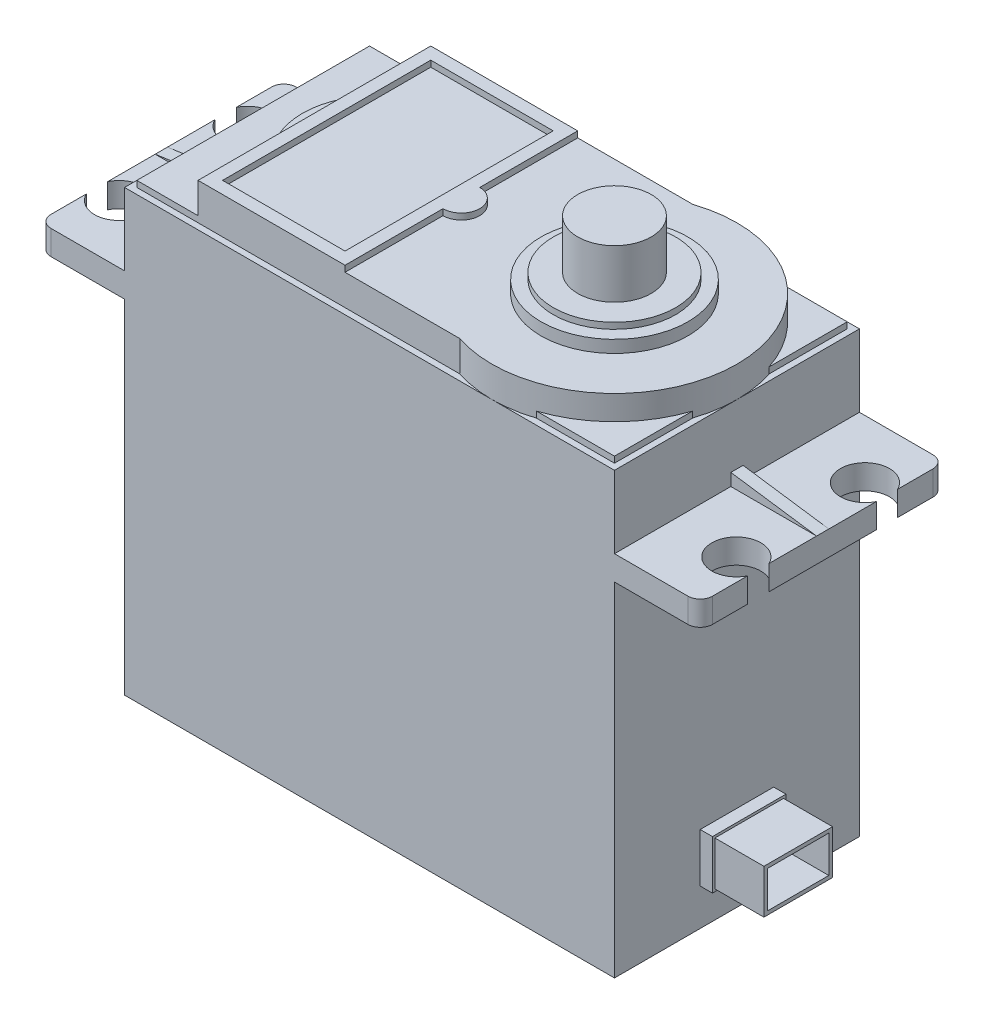
SolidWorks part; units mm, degrees
ref_plane "Front Plane" through (0, 0, 0) normal (0, 0, 1) x (1, 0, 0)
ref_plane "Top Plane" through (0, 0, 0) normal (0, 1, 0) x (1, 0, 0)
ref_plane "Right Plane" through (0, 0, 0) normal (1, 0, 0) x (0, 0, -1)
sketch "Sketch1" plane through (0, 0, 0) normal (0, 1, 0) x (1, 0, 0)
  line L1 (0, 0) -> (40, 0)
  line L2 (0, 0) -> (0, 20)
  line L3 (0, 20) -> (40, 20)
  line L4 (40, 0) -> (40, 20)
  dimension "D1" = 40
  dimension "D2" = 20
extrude "Boss-Extrude1" add sketch "Sketch1" along normal blind 35.9
sketch "Sketch2" plane through (0, 0, 0) normal (1, 0, 0) x (0, 0, -1)
  line L0 (0, 35.9) -> (0, 0) construction
  line L1 (0, 28) -> (20, 28)
  line L2 (0, 28) -> (0, 30)
  line L3 (0, 30) -> (20, 30)
  line L4 (20, 28) -> (20, 30)
  line L5 (20, 35.9) -> (20, 0) construction
  line L7 (0, 0) -> (20, 0) construction
  dimension "D1" = 28
  dimension "D2" = 2
extrude "Boss-Extrude2" add sketch "Sketch2" against normal blind 7
sketch "Sketch3" plane through (0, 30, 0) normal (0, 1, 0) x (1, 0, 0)
  line L0 (-7, 20) -> (-7, 0) construction
  line L1 (-7, 10.5) -> (0, 10.5)
  line L2 (-7, 10.5) -> (-7, 9.5)
  line L3 (-7, 9.5) -> (0, 9.5)
  line L4 (0, 10.5) -> (0, 9.5)
  line L5 (0, 20) -> (0, 0) construction
  line L6 (-7, 20) -> (-7, 0) construction
  point P8 (-7, 10)
  point P9 (-7, 10)
  dimension "D1" = 1
extrude "Boss-Extrude3" add sketch "Sketch3" along normal blind 1
sketch "Sketch4" plane through (0, 30, 0) normal (0, 1, 0) x (1, 0, 0)
  line L1 (-7, 20) -> (-7, 10.5) construction
  line L3 (-7, 10.5) -> (-7, 9.5) construction
  line L4 (-7, 10) -> (0, 10) construction
  line L5 (0, 20) -> (0, 0) construction
  circle A0 centre (-5.2, 15.25) radius 2
  circle A1 centre (-5.2, 4.75) radius 2
  point P3 (-7, 15.25)
  dimension "D1" = 4
  dimension "D2" = 1.8
extrude "Cut-Extrude1" cut sketch "Sketch4" against normal up to next
fillet "Fillet1" radius 1 2 edges at (-7, 29, 0) (-7, 29, -20)
sketch "Sketch5" plane through (0, 0, -9.5) normal (0, 0, 1) x (1, 0, 0)
  line L0 (-7, 30) -> (0, 31)
  line L5 (-7, 30) -> (-7, 31)
  line L6 (-7, 31) -> (0, 31)
extrude "Cut-Extrude2" cut sketch "Sketch5" against normal blind 11
ref_plane "Plane1" through (20, 0, 0) normal (1, 0, 0) x (0, 0, -1)
mirror "Mirror1" about plane through (20, 0, 0) normal (1, 0, 0) of "Cut-Extrude2", "Fillet1", "Cut-Extrude1", "Boss-Extrude3", "Boss-Extrude2"
sketch "Sketch6" plane through (0, 35.9, 0) normal (0, 1, 0) x (1, 0, 0)
  line L4 (0, 20) -> (0, 0) construction
  line L32 (0.5, 19.5) -> (0.5, 0.5)
  line L33 (0.5, 0.5) -> (39.5, 0.5)
  line L34 (39.5, 0.5) -> (39.5, 19.5)
  line L35 (39.5, 19.5) -> (0.5, 19.5)
  line L36 (0.5, 19.5) -> (0.5, 0.5)
  line L37 (0.5, 0.5) -> (39.5, 0.5)
  line L38 (39.5, 0.5) -> (39.5, 19.5)
  line L39 (39.5, 19.5) -> (0.5, 19.5)
  point P2 (0, 10)
  point P3 (0, 0)
  dimension "D1" = 0.5
extrude "Boss-Extrude4" add sketch "Sketch6" along normal blind 0.5
sketch "Sketch7" plane through (0, 36.4, 0) normal (0, 1, 0) x (1, 0, 0)
  line L0 (39.5, 19.5) -> (0.5, 19.5) construction
  line L1 (5.5, 19.5) -> (30.5, 19.5)
  line L2 (5.5, 19.5) -> (5.5, 13.2826)
  line L3 (5.5, 0.5) -> (30.5, 0.5)
  line L4 (30.5, 19.5) -> (30.5, 0.5)
  line L5 (0.5, 0.5) -> (39.5, 0.5) construction
  line L6 (0.5, 19.5) -> (0.5, 0.5) construction
  line L7 (4.5, 10) -> (4.5, 5.32) construction
  line L8 (5.5, 6.7174) -> (5.5, 0.5)
  circle A0 centre (10.5, 10) radius 6 construction
  arc A1 (5.5, 13.2826) -> (5.5, 6.7174) centre (10.5, 10) ccw
  dimension "D3" = 2
  dimension "D4" = 12
  dimension "D1" = 25
  dimension "D2" = 5
extrude "Boss-Extrude5" add sketch "Sketch7" along normal blind 2
sketch "Sketch8" plane through (0, 38.4, 0) normal (0, 1, 0) x (1, 0, 0)
  line L0 (40, 20) -> (0, 20) construction
  line L1 (40, 0) -> (40, 20) construction
  circle A0 centre (30, 10) radius 10
  point P2 (29.8695, 9.9045)
  point P3 (23.6294, 10.3502)
  dimension "D1" = 20
extrude "Boss-Extrude6" add sketch "Sketch8" against normal blind 2.5
sketch "Sketch9" plane through (0, 38.4, 0) normal (0, 1, 0) x (1, 0, 0)
  circle A0 centre (30, 10) radius 6
  arc A1 (26.8775, 0.5) -> (26.8775, 19.5) centre (30, 10) ccw construction
  point P2 (23.8841, 9.9045)
  point P3 (26.6221, 11.178)
  dimension "D1" = 12
extrude "Boss-Extrude7" add sketch "Sketch9" along normal blind 1
sketch "Sketch10" plane through (0, 39.4, 0) normal (0, 1, 0) x (1, 0, 0)
  circle A0 centre (30, 10) radius 5
  circle A1 centre (30, 10) radius 6 construction
  dimension "D1" = 1
extrude "Boss-Extrude8" add sketch "Sketch10" along normal blind 0.5
sketch "Sketch11" plane through (0, 38.4, 0) normal (0, 1, 0) x (1, 0, 0)
  line L1 (5.5, 0.5) -> (17.5, 0.5)
  line L2 (5.5, 0.5) -> (5.5, 19.5)
  line L3 (5.5, 19.5) -> (17.5, 19.5)
  line L4 (17.5, 0.5) -> (17.5, 8.5)
  line L5 (26.8775, 19.5) -> (5.5, 19.5) construction
  line L6 (16.5, 1.5) -> (16.5, 18.5)
  line L7 (6.5, 18.5) -> (16.5, 18.5)
  line L8 (6.5, 1.5) -> (6.5, 18.5)
  line L9 (6.5, 1.5) -> (16.5, 1.5)
  line L10 (17.5, 11.5) -> (17.5, 19.5)
  line L11 (17.5, 0.5) -> (17.5, 19.5) construction
  arc A0 (17.5, 8.5) -> (17.5, 11.5) centre (17.5, 10) ccw
  point P4 (0, 0)
  point P7 (0, 0)
  dimension "D3" = 3
  dimension "D1" = 12
  dimension "D2" = 1
extrude "Boss-Extrude9" add sketch "Sketch11" along normal blind 0.5
sketch "Sketch12" plane through (0, 39.9, 0) normal (0, 1, 0) x (1, 0, 0)
  circle A0 centre (30, 10) radius 3
  dimension "D1" = 6
extrude "Boss-Extrude10" add sketch "Sketch12" along normal blind 4
sketch "Sketch13" plane through (40, 0, 0) normal (1, 0, 0) x (0, 0, -1)
  line L0 (0, 0) -> (20, 0) construction
  line L1 (7, 7) -> (13, 7)
  line L2 (7, 7) -> (7, 3)
  line L3 (7, 3) -> (13, 3)
  line L4 (13, 7) -> (13, 3)
  line L5 (0, 0) -> (20, 0) construction
  point P10 (10, 0)
  point P11 (10, 3)
  dimension "D1" = 4
  dimension "D2" = 6
  dimension "D3" = 7
extrude "Boss-Extrude11" add sketch "Sketch13" along normal blind 1
sketch "Sketch14" plane through (41, 0, 0) normal (1, 0, 0) x (0, 0, -1)
  line L0 (7.2, 6.8) -> (7.2, 3.2)
  line L1 (7.2, 3.2) -> (12.8, 3.2)
  line L2 (12.8, 3.2) -> (12.8, 6.8)
  line L3 (12.8, 6.8) -> (7.2, 6.8)
  line L4 (7, 7) -> (7, 3)
  line L5 (7, 3) -> (13, 3)
  line L6 (13, 3) -> (13, 7)
  line L7 (13, 7) -> (7, 7)
  line L8 (7, 7) -> (7, 3) construction
  line L9 (7, 3) -> (13, 3) construction
  line L10 (13, 3) -> (13, 7) construction
  line L11 (13, 7) -> (7, 7) construction
  line L12 (12.5, 6.5) -> (7.5, 6.5)
  line L13 (7.5, 6.5) -> (7.5, 3.5)
  line L14 (7.5, 3.5) -> (12.5, 3.5)
  line L15 (12.5, 3.5) -> (12.5, 6.5)
  dimension "D1" = 0
  dimension "D2" = 0.2
  dimension "D3" = 0.3
extrude "Boss-Extrude12" add sketch "Sketch14" along normal blind 4
